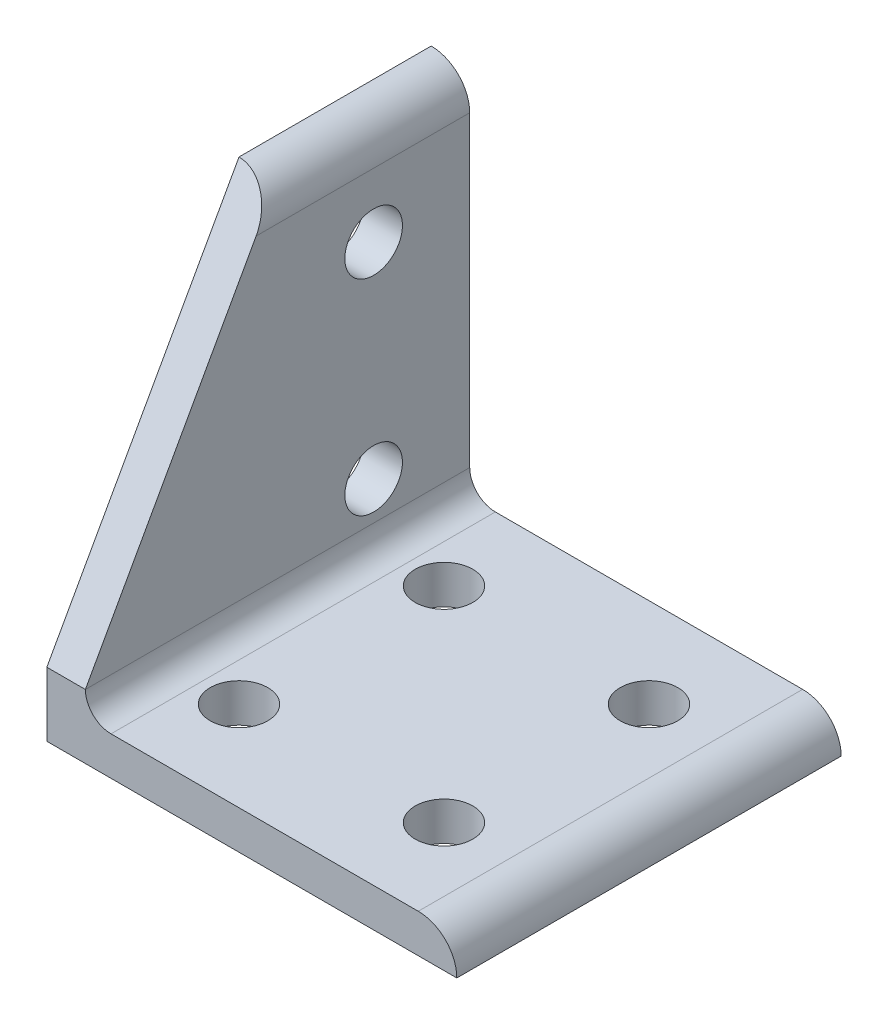
SolidWorks part; units mm, degrees
ref_plane "Front Plane" through (0, 0, 0) normal (0, 0, 1) x (1, 0, 0)
ref_plane "Top Plane" through (0, 0, 0) normal (0, 1, 0) x (1, 0, 0)
ref_plane "Right Plane" through (0, 0, 0) normal (1, 0, 0) x (0, 0, -1)
sketch "Sketch1" plane through (0, 0, 0) normal (0, 0, 1) x (1, 0, 0)
  line L0 (25.4, -25.4) -> (-25.4, -25.4) construction
  line L1 (-25.4, 25.4) -> (-25.4, -25.4) construction
  line L2 (25.4, -25.4) -> (25.4, -20.6248) construction
  point P3 (0, -25.4)
  point P6 (-25.4, 0)
  dimension "Length" = 50.8
  dimension "Thickness" = 4.7752
sketch "Sketch2" plane through (0, 0, 0) normal (1, 0, 0) x (0, 0, -1)
  line L0 (23.8125, 0) -> (-23.8125, 0) construction
  line L1 (0, 25.4) -> (23.8125, 25.4) construction
  line L2 (11.9062, 25.4) -> (11.9062, 12.7) construction
  line L3 (8.3375, 12.7) -> (15.475, 12.7) construction
  point P10 (0, 0)
  point P13 (0, 25.4)
  point P19 (11.9062, 12.7)
  dimension "Width" = 47.625
  dimension "Hole Dia" = 7.1374
  dimension "Hole Spacing" = 25.4
sketch "Sketch3" plane through (0, 0, 0) normal (0, 1, 0) x (1, 0, 0)
  line L1 (25.4, 0) -> (-25.4, 0) construction
  line L2 (25.4, 0) -> (-25.4, 0) construction
  point P0 (-12.7, 12.7)
  dimension "Hole to Edge" = 12.7
  dimension "D1" = 25.4
sketch "Sketch4" plane through (0, 0, 0) normal (0, 0, 1) x (1, 0, 0)
  line L0 (-25.4, 25.4) -> (-25.4, -25.4)
  line L1 (-25.4, -25.4) -> (25.4, -25.4)
  line L2 (-20.6248, 20.6248) -> (-20.6248, -17.4498)
  line L3 (-17.4498, -20.6248) -> (20.6248, -20.6248)
  arc A0 (-20.6248, -17.4498) -> (-17.4498, -20.6248) centre (-17.4498, -17.4498) ccw
  arc A1 (20.6248, -20.6248) -> (25.4, -25.4) centre (20.6248, -25.4) cw
  arc A2 (-20.6248, 20.6248) -> (-25.4, 25.4) centre (-25.4, 20.6248) ccw
  dimension "Radius" = 3.175
extrude "Boss-Extrude1" add sketch "Sketch4" against normal up to vertex (23.8125 mm away) and the other way up to vertex (23.8125 mm away) up to point (0, 0, -23.8125) other way up to point (0, 0, 23.8125)
sketch "Sketch5" plane through (-20.6248, 0, 0) normal (1, 0, 0) x (0, 0, -1)
  line L14 (0, 25.4) -> (-23.8125, 25.4)
  line L15 (-23.8125, 25.4) -> (-23.8125, 20.6248) construction
  line L16 (-23.8125, 25.4) -> (-23.8125, -17.4498)
  line L17 (-23.8125, -17.4498) -> (0, 25.4)
extrude "Cut-Extrude1" cut sketch "Sketch5" against normal through all both and the other way through all
sketch "Sketch6" plane through (-20.6248, 0, 0) normal (1, 0, 0) x (0, 0, -1)
  line L0 (8.3375, 12.7) -> (15.475, 12.7) construction
  line L1 (23.8125, 0) -> (-23.8125, 0) construction
  line L2 (23.8125, 0) -> (-23.8125, 0) construction
  circle A0 centre (11.9063, 12.7) radius 3.5687
  circle A1 centre (11.9063, -12.7) radius 3.5687
extrude "Cut-Extrude2" cut sketch "Sketch6" against normal through all
sketch "Sketch7" plane through (0, -20.6248, 0) normal (0, 1, 0) x (1, 0, 0)
  line L0 (25.4, 0) -> (-25.4, 0) construction
  line L1 (25.4, 0) -> (-25.4, 0) construction
  circle A0 centre (-12.7, 12.7) radius 3.5687
  circle A1 centre (12.7, 12.7) radius 3.5687
  circle A2 centre (12.7, -12.7) radius 3.5687
  circle A3 centre (-12.7, -12.7) radius 3.5687
  dimension "D1" = 7.1374
  dimension "D2" = 25.4
extrude "Cut-Extrude3" cut sketch "Sketch7" against normal through all
equation "\"D1@Sketch3\" = \"Hole Spacing@Sketch2\""
equation "\"D1@Sketch7\"=\"Hole Dia@Sketch2\""
equation "\"D2@Sketch7\"=\"Hole Spacing@Sketch2\""
